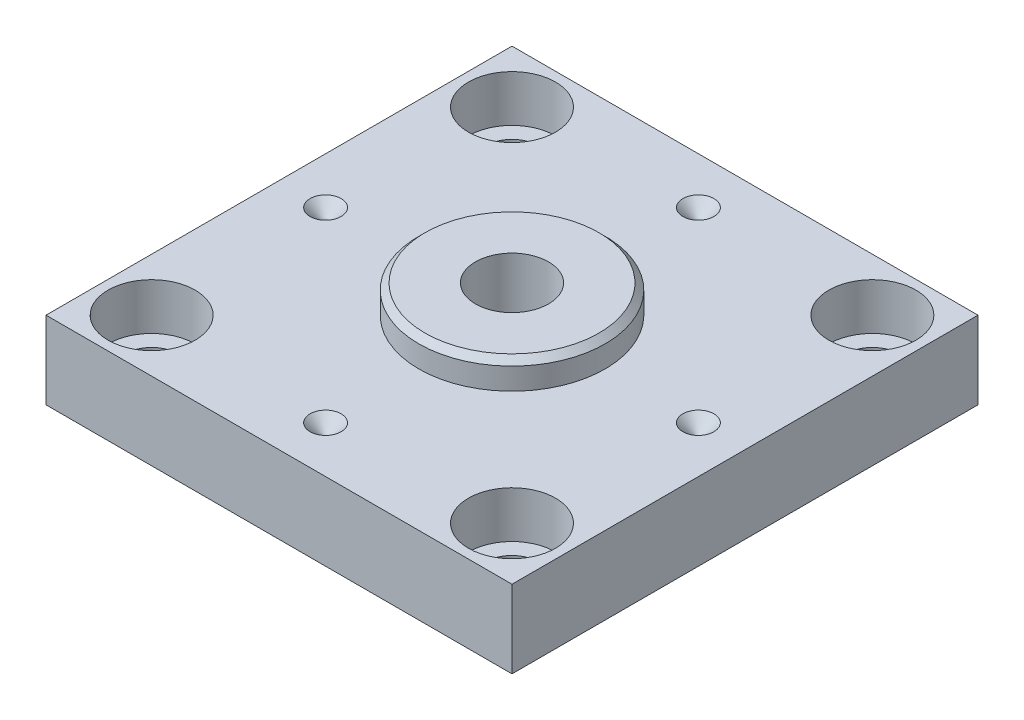
SolidWorks part; units mm, degrees
material "Plain Carbon Steel"
ref_plane "Front Plane" through (0, 0, 0) normal (0, 0, 1) x (1, 0, 0)
ref_plane "Top Plane" through (0, 0, 0) normal (0, 1, 0) x (1, 0, 0)
ref_plane "Right Plane" through (0, 0, 0) normal (1, 0, 0) x (0, 0, -1)
sketch "Sketch1" plane through (0, 0, 0) normal (0, 1, 0) x (1, 0, 0)
  line L1 (-75, -75) -> (75, -75)
  line L2 (-75, -75) -> (-75, 75)
  line L3 (-75, 75) -> (75, 75)
  line L4 (75, -75) -> (75, 75)
  line L5 (-75, -75) -> (75, 75) construction
  line L6 (-75, 75) -> (75, -75) construction
  point P0 (0, 0)
  dimension "D1" = 150
  dimension "D2" = 150
extrude "Boss-Extrude1" add sketch "Sketch1" along normal blind 25
sketch "Sketch2" plane through (0, 25, 0) normal (0, 1, 0) x (1, 0, 0)
  circle A0 centre (0, 0) radius 30
  dimension "D1" = 60
extrude "Boss-Extrude2" add sketch "Sketch2" along normal blind 9
chamfer "Chamfer1" distance 2 angle 45 1 edges at (0, 34, 30)
hole_wizard "M25x1.5 Tapped Hole1" positions "Sketch3" profile "Sketch4" tap size "M25x1.5" standard "DIN" end condition through all
sketch "Sketch3" plane through (0, 34, 0) normal (0, 1, 0) x (1, 0, 0)
  point P0 (0, 0)
sketch "Sketch4" plane through (0, 34, 0) normal (1, 0, 0) x (0, 0, 1)
  line L0 (0, 0) -> (0, 34)
  line L1 (0, 34) -> (11.75, 34)
  line L2 (11.75, 34) -> (11.75, 0)
  line L5 (11.75, 0) -> (0, 0)
  line L11 (0, -6.35) -> (0, 107.95) construction
  dimension "Thru Tap Drill Dia." = 23.5
  dimension "Thru Tap Drill Depth" = 34
cosmetic thread "Hole Thread1" parameters "D2"=25
hole_wizard "Hole1" positions "Sketch5" profile "Sketch6" legacy end condition through all
sketch "Sketch5" plane through (0, 25, 0) normal (0, 1, 0) x (1, 0, 0)
  line L0 (0, 36.0178) -> (0, 0) construction
  line L1 (0, 0) -> (-38.3347, 0) construction
  point P0 (-58, 58)
  point P2 (58, 58)
  point P4 (-58, -58)
  point P6 (58, -58)
  point P28 (0, 0)
  dimension "D1" = 116
  dimension "D2" = 116
sketch "Sketch6" plane through (-58, 25, -58) normal (1, 0, 0) x (0, 0, 1)
  line L0 (0, 0) -> (0, 25)
  line L1 (0, 25) -> (8.5, 25)
  line L2 (8.5, 25) -> (8.5, 15)
  line L3 (8.5, 15) -> (14, 15)
  line L4 (14, 15) -> (14, 0)
  line L5 (14, 0) -> (0, 0)
  line L6 (0, 110) -> (0, -10) construction
  dimension "Diameter" = 17
  dimension "Depth" = 25
  dimension "C-Bore Diameter" = 28
  dimension "C-Bore Depth" = 15
sketch "Sketch7" plane through (0, 0, 0) normal (0, 0, 1) x (1, 0, 0)
  line L0 (-65, 25) -> (-60, 20)
  line L1 (-75, 25) -> (75, 25) construction
  line L4 (-65, 25) -> (-60, 25)
  line L5 (-60, 25) -> (-60, 20)
  line L6 (-60, 28.2263) -> (-60, 18.1813) construction
  dimension "D2" = 60
revolve "Cut-Revolve1" cut sketch "Sketch7" angle 360 about L6
pattern_circular "CirPattern1" count 4 over 360 about axis through (0, 0, 0) along (0, 1, 0) of "Cut-Revolve1"
